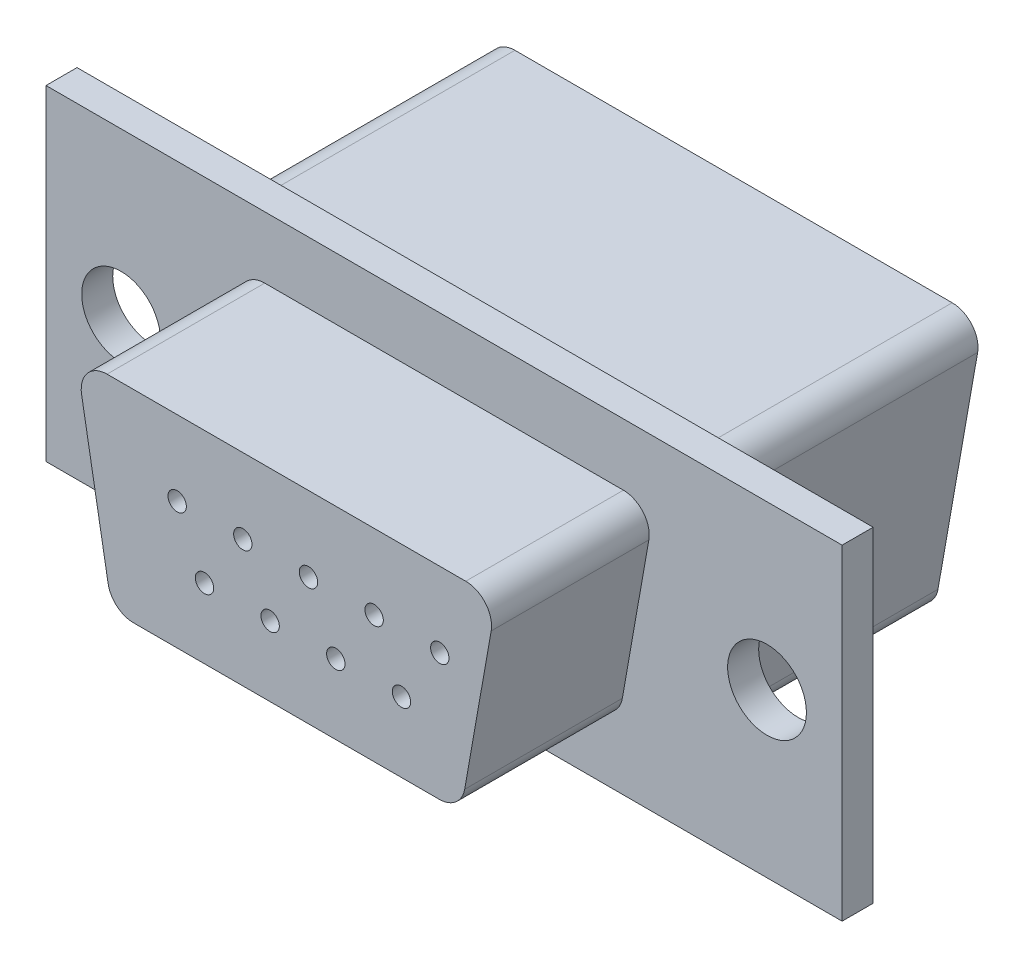
SolidWorks part; units mm, degrees
ref_plane "正面" through (0, 0, 0) normal (0, 0, 1) x (1, 0, 0)
ref_plane "平面" through (0, 0, 0) normal (0, 1, 0) x (1, 0, 0)
ref_plane "右側面" through (0, 0, 0) normal (1, 0, 0) x (0, 0, -1)
sketch "ｽｹｯﾁ1" plane through (0, 0, 0) normal (0, 0, 1) x (1, 0, 0)
  line L1 (-15.4, -6.3) -> (15.4, -6.3)
  line L2 (-15.4, -6.3) -> (-15.4, 6.3)
  line L3 (-15.4, 6.3) -> (15.4, 6.3)
  line L4 (15.4, -6.3) -> (15.4, 6.3)
  line L5 (-15.4, -6.3) -> (15.4, 6.3) construction
  line L6 (-15.4, 6.3) -> (15.4, -6.3) construction
  point P0 (0, 0)
  dimension "D1" = 30.8
  dimension "D2" = 12.6
extrude "ﾎﾞｽ - 押し出し1" add sketch "ｽｹｯﾁ1" along normal blind 1.2
sketch "ｽｹｯﾁ2" plane through (0, 0, 1.2) normal (0, 0, 1) x (1, 0, 0)
  line L0 (-8.13, 9.2752) -> (-8.13, -7.7701) construction
  line L1 (-6.7511, -3.91) -> (6.7511, -3.91)
  line L2 (-6.7511, -3.91) -> (-8.13, 3.91)
  line L3 (-8.13, 3.91) -> (8.13, 3.91)
  line L4 (6.7511, -3.91) -> (8.13, 3.91)
  line L5 (8.13, 9.2752) -> (8.13, -7.4612) construction
  point P0 (0, 0)
  dimension "D1" = 8.13
  dimension "D2" = 3.91
  dimension "D4" = 3.91
  dimension "D3" = 8.13
  dimension "D5" = 10
  dimension "D6" = 10
extrude "ﾎﾞｽ - 押し出し2" add sketch "ｽｹｯﾁ2" along normal blind 6.1
sketch "ｽｹｯﾁ3" plane through (0, 0, 0) normal (0, 0, -1) x (-1, 0, 0)
  line L0 (-9.65, 12.7623) -> (-9.65, -10.5928) construction
  line L1 (-7.7633, -5.35) -> (7.7633, -5.35)
  line L2 (-7.7633, -5.35) -> (-9.65, 5.35)
  line L3 (-9.65, 5.35) -> (9.65, 5.35)
  line L4 (7.7633, -5.35) -> (9.65, 5.35)
  line L7 (9.65, 13.0912) -> (9.65, -9.6882) construction
  point P0 (0, 0)
  dimension "D1" = 9.65
  dimension "D2" = 5.35
  dimension "D3" = 9.65
  dimension "D4" = 5.35
  dimension "D5" = 10
  dimension "D6" = 10
extrude "ﾎﾞｽ - 押し出し3" add sketch "ｽｹｯﾁ3" along normal blind 10
hole_wizard "#0000 すきま穴1" positions "3Dｽｹｯﾁ1" profile "ｽｹｯﾁ5" hole size "#0000" standard "Ansi Inch"
sketch3d "3Dｽｹｯﾁ1"
  point P0 (-4.2254, 1.008, 1.2)
sketch "ｽｹｯﾁ5" plane through (-4.2254, 1.008, 1.2) normal (1, 0, 0) x (0, 1, 0)
  line L0 (0, 0) -> (0, 6.1)
  line L1 (0, 6.1) -> (0.3556, 6.1)
  line L2 (0.3556, 6.1) -> (0.3556, 0)
  line L5 (0.3556, 0) -> (0, 0)
  line L11 (0, -6.35) -> (0, 107.95) construction
  dimension "通し穴の直径" = 0.7112
  dimension "通し穴の深さ" = 6.1
hole_wizard "#0000 すきま穴2" positions "3Dｽｹｯﾁ2" profile "ｽｹｯﾁ6" hole size "#0000" standard "Ansi Inch"
sketch3d "3Dｽｹｯﾁ2"
  point P0 (-3.1683, -1.2028, 1.2)
sketch "ｽｹｯﾁ6" plane through (-3.1683, -1.2028, 1.2) normal (1, 0, 0) x (0, 1, 0)
  line L0 (0, 0) -> (0, 6.1)
  line L1 (0, 6.1) -> (0.3556, 6.1)
  line L2 (0.3556, 6.1) -> (0.3556, 0)
  line L5 (0.3556, 0) -> (0, 0)
  line L11 (0, -6.35) -> (0, 107.95) construction
  dimension "通し穴の直径" = 0.7112
  dimension "通し穴の深さ" = 6.1
pattern_linear "直線ﾊﾟﾀｰﾝ1" count 5 spacing 2.54 along (1, 0, 0) of "#0000 すきま穴1"
pattern_linear "直線ﾊﾟﾀｰﾝ2" count 4 spacing 2.54 along (1, 0, 0) of "#0000 すきま穴2"
sketch "ｽｹｯﾁ8" plane through (0, 0, 1.2) normal (0, 0, 1) x (1, 0, 0)
  point P0 (-12.495, 0)
  point P1 (12.495, 0)
  dimension "D1" = 12.495
  dimension "D2" = 12.495
hole_wizard "#3 すきま穴2" positions "3Dｽｹｯﾁ4" profile "ｽｹｯﾁ9" hole size "#3" standard "Ansi Inch" end condition through all
sketch3d "3Dｽｹｯﾁ4"
  point P0 (-12.495, 0, 1.2)
  point P3 (12.495, 0, 1.2)
sketch "ｽｹｯﾁ9" plane through (-12.495, 0, 1.2) normal (1, 0, 0) x (0, -1, 0)
  line L0 (0, 0) -> (0, 11.2)
  line L1 (0, 11.2) -> (1.524, 11.2)
  line L2 (1.524, 11.2) -> (1.524, 0)
  line L5 (1.524, 0) -> (0, 0)
  line L11 (0, -6.35) -> (0, 107.95) construction
  dimension "通し穴の直径" = 3.048
  dimension "通し穴の深さ" = 11.2
fillet "ﾌｨﾚｯﾄ1" radius 1 8 edges at (-8.13, 3.91, 4.25) (-6.7511, -3.91, 4.25) (8.13, 3.91, 4.25) (6.7511, -3.91, 4.25) (7.7633, -5.35, -5) (9.65, 5.35, -5) (-7.7633, -5.35, -5) (-9.65, 5.35, -5)
